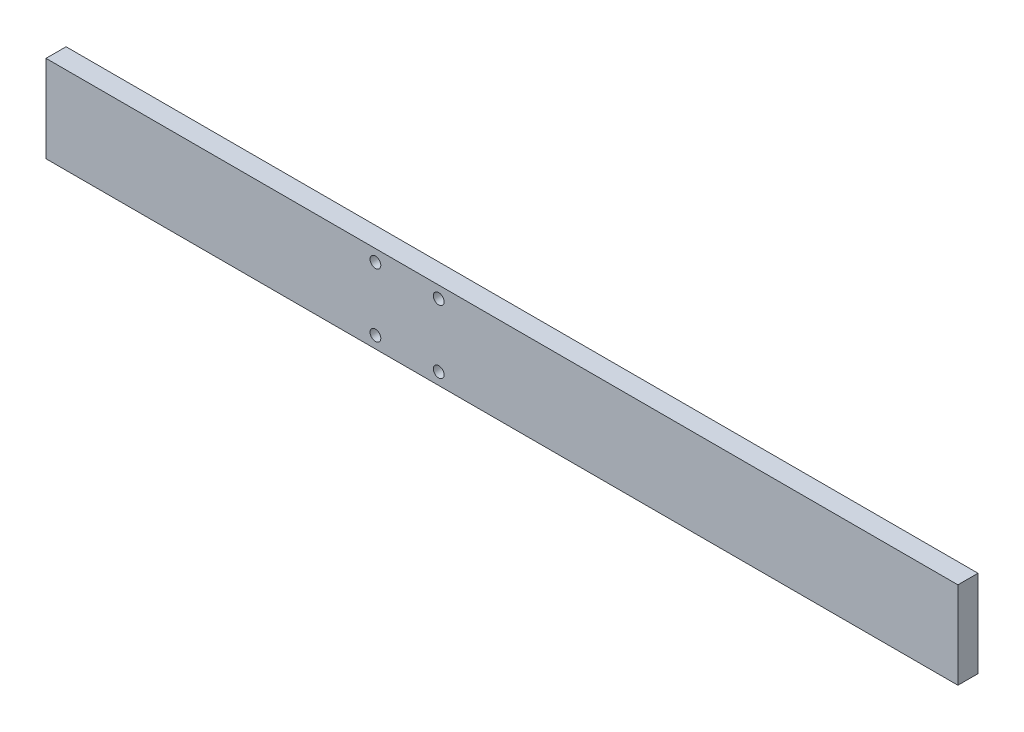
SolidWorks part; units mm, degrees
ref_plane "Front Plane" through (0, 0, 0) normal (0, 0, 1) x (1, 0, 0)
ref_plane "Top Plane" through (0, 0, 0) normal (0, 1, 0) x (1, 0, 0)
ref_plane "Right Plane" through (0, 0, 0) normal (1, 0, 0) x (0, 0, -1)
sketch "Sketch1" plane through (0, 0, 0) normal (0, 0, 1) x (1, 0, 0)
  line B0 (242.29, 0) -> (288.29, 0)
  line B1 (288.29, 27.5) -> (0, 27.5)
  line B2 (0, 27.5) -> (0, 0)
  line B3 (0, 0) -> (242.29, 0)
  line B4 (288.29, 0) -> (288.29, 27.5)
  circle B5 centre (104.145, 3.75) radius 1.7
  circle B6 centre (124.145, 3.75) radius 1.7
  circle B7 centre (124.145, 23.75) radius 1.7
  circle B8 centre (104.145, 23.75) radius 1.7
sketch_block_instance "Bearing_Side-1"
sketch_block "Bearing_Side" parameters "D1"=3.4, "D2"=20, "D3"=20
extrude "Boss-Extrude1" add sketch "Sketch1" along normal blind 6.35
